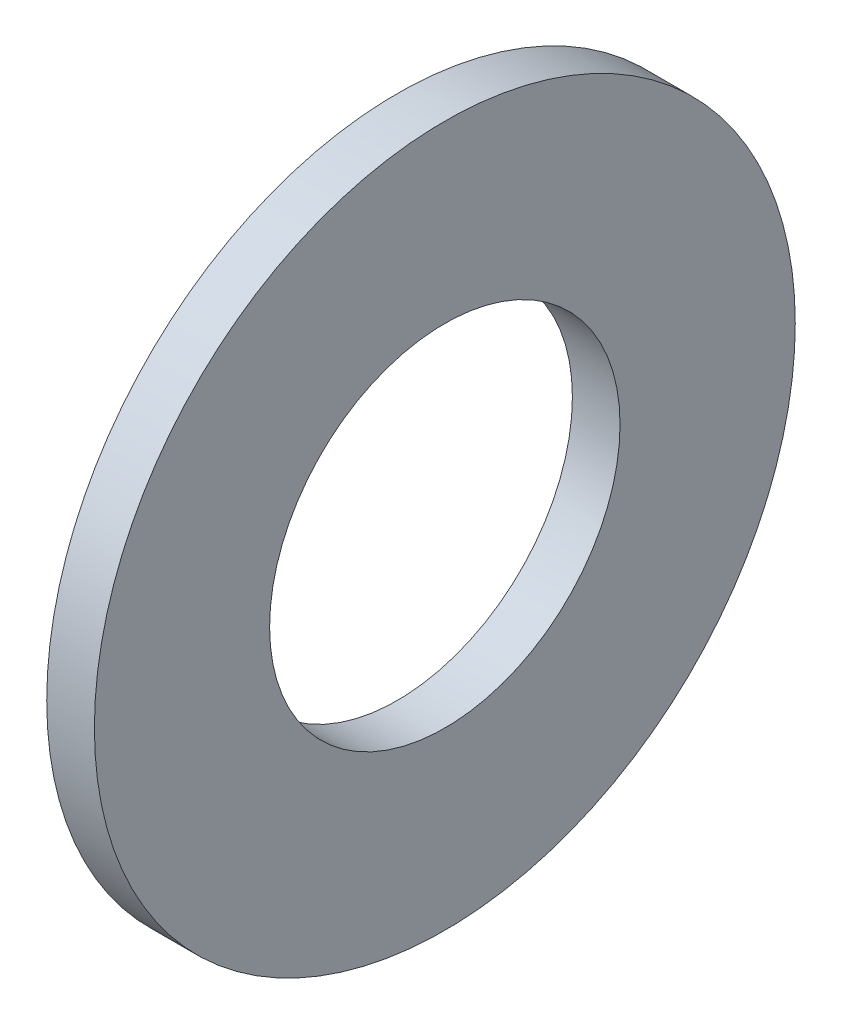
SolidWorks part; units mm, degrees
ref_plane "Front Plane" through (0, 0, 0) normal (0, 0, 1) x (1, 0, 0)
ref_plane "Top Plane" through (0, 0, 0) normal (0, 1, 0) x (1, 0, 0)
ref_plane "Right Plane" through (0, 0, 0) normal (1, 0, 0) x (0, 0, -1)
sketch "Sketch1" plane through (0, 0, 0) normal (1, 0, 0) x (0, 0, -1)
  circle A0 centre (0, 0) radius 3.175
  circle A1 centre (0, 0) radius 6.35
  dimension "OD" = 6.35
  dimension "ID" = 12.7
extrude "Boss-Extrude1" add sketch "Sketch1" along normal blind 0.8636
